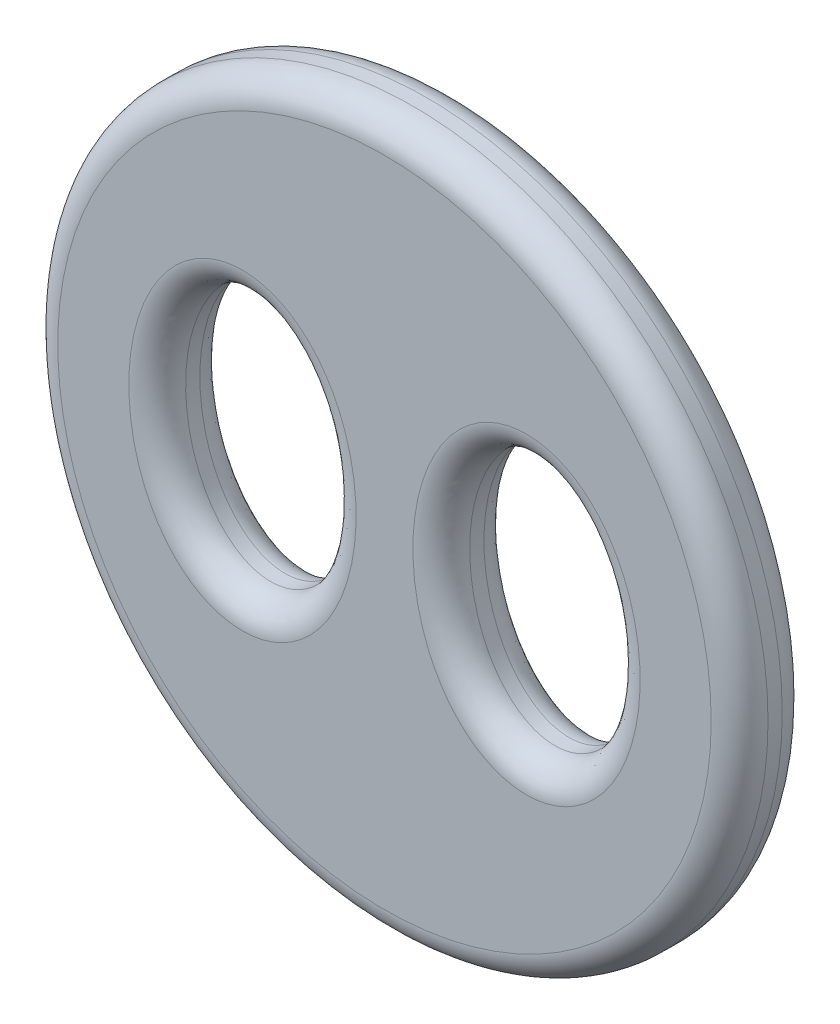
SolidWorks part; units mm, degrees
ref_plane "Front Plane" through (0, 0, 0) normal (0, 0, 1) x (1, 0, 0)
ref_plane "Top Plane" through (0, 0, 0) normal (0, 1, 0) x (1, 0, 0)
ref_plane "Right Plane" through (0, 0, 0) normal (1, 0, 0) x (0, 0, -1)
sketch "Sketch1" plane through (0, 0, 0) normal (0, 0, 1) x (1, 0, 0)
  line L0 (0, 34.4348) -> (0, -34.362) construction
  line L1 (30.2691, 0) -> (-35.0609, 0) construction
  circle A0 centre (0, 0) radius 25
  ellipse E0 centre (10, 0) end of major axis (10, -9) minor radius 6
  ellipse E1 centre (-10, 0) end of major axis (-10, 9) minor radius 6
  point P8 (0, 0)
  point P14 (0, 0)
  point P15 (-0.6023, 0)
  point P16 (10.556, 0)
  dimension "D1" = 50
  dimension "D2" = 9
  dimension "D3" = 6
  dimension "D4" = 10
extrude "Boss-Extrude1" add sketch "Sketch1" along normal blind 5
fillet "Fillet1" radius 2 2 edges at (25, 0, 0) (25, 0, 5)
fillet "Fillet2" radius 2 4 edges at (10, -9, 5) (10, -9, 0) (-10, -9, 0) (-10, -9, 5)
